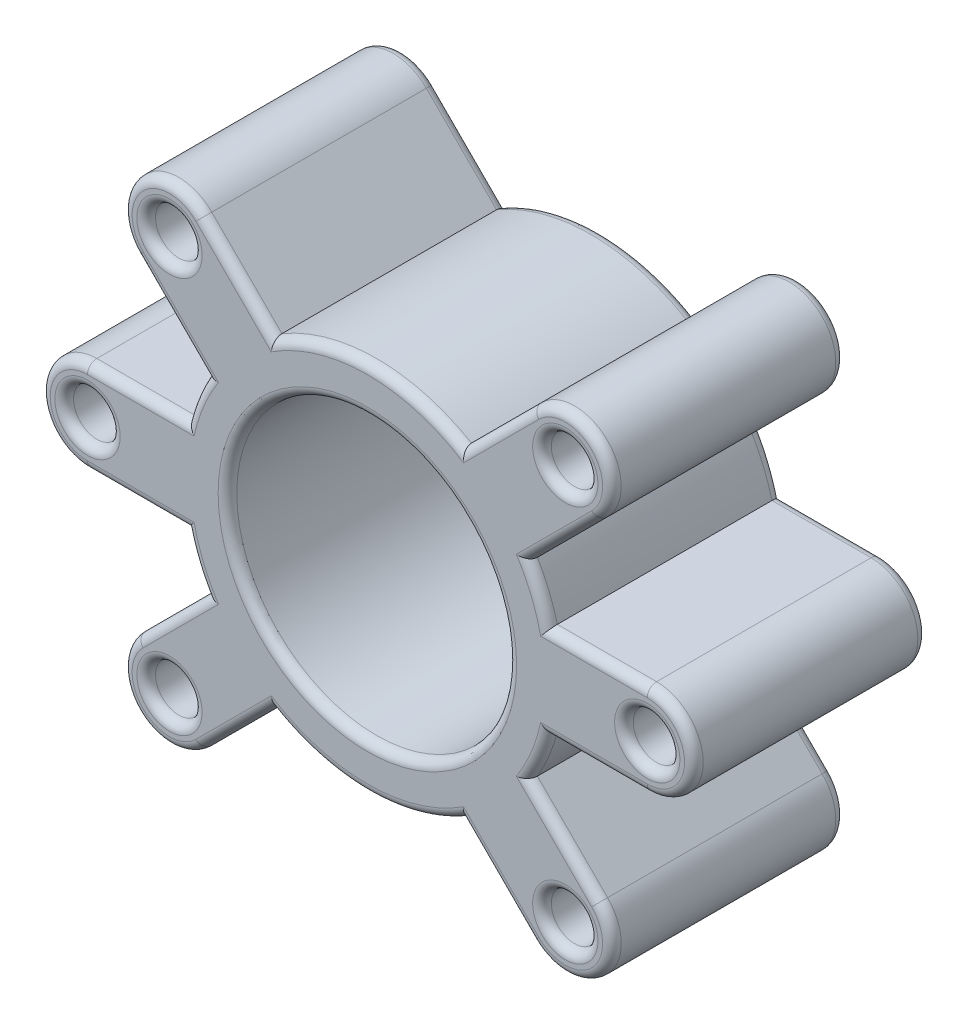
SolidWorks part; units mm, degrees
ref_plane "Front Plane" through (0, 0, 0) normal (0, 0, 1) x (1, 0, 0)
ref_plane "Top Plane" through (0, 0, 0) normal (0, 1, 0) x (1, 0, 0)
ref_plane "Right Plane" through (0, 0, 0) normal (1, 0, 0) x (0, 0, -1)
sketch "Sketch1" plane through (0, 0, 0) normal (0, 0, 1) x (1, 0, 0)
  line L0 (0, 0) -> (68535.6962, 0) construction
  line L1 (0, 0) -> (0, 68535.6962) construction
  line L2 (38.7298, 10) -> (60, 10)
  line L3 (60, -10) -> (38.7298, -10)
  line L4 (34.4572, -20.3151) -> (49.4975, -35.3553)
  line L5 (35.3553, -49.4975) -> (20.3151, -34.4572)
  line L6 (10, -38.7298) -> (10, -60) [skipped]
  line L7 (-10, -60) -> (-10, -38.7298) [skipped]
  line L8 (-20.3151, -34.4572) -> (-35.3553, -49.4975)
  line L9 (-49.4975, -35.3553) -> (-34.4572, -20.3151)
  line L10 (-38.7298, -10) -> (-60, -10)
  line L11 (-60, 10) -> (-38.7298, 10)
  line L12 (-34.4572, 20.3151) -> (-49.4975, 35.3553)
  line L13 (-35.3553, 49.4975) -> (-20.3151, 34.4572)
  line L14 (-10, 38.7298) -> (-10, 60) [skipped]
  line L15 (10, 60) -> (10, 38.7298) [skipped]
  line L16 (20.3151, 34.4572) -> (35.3553, 49.4975)
  line L17 (49.4975, 35.3553) -> (34.4572, 20.3151)
  circle A0 centre (0, 0) radius 30
  circle A1 centre (0, 0) radius 60 construction
  circle A2 centre (0, 0) radius 40
  arc A3 (60, 10) -> (60, -10) centre (60, 0) cw
  circle A4 centre (60, 0) radius 5
  arc A5 (49.4975, -35.3553) -> (35.3553, -49.4975) centre (42.4264, -42.4264) cw
  circle A6 centre (42.4264, -42.4264) radius 5
  arc A7 (10, -60) -> (-10, -60) centre (0, -60) cw [skipped]
  circle A8 centre (0, -60) radius 5 [skipped]
  arc A9 (-35.3553, -49.4975) -> (-49.4975, -35.3553) centre (-42.4264, -42.4264) cw
  circle A10 centre (-42.4264, -42.4264) radius 5
  arc A11 (-60, -10) -> (-60, 10) centre (-60, 0) cw
  circle A12 centre (-60, 0) radius 5
  arc A13 (-49.4975, 35.3553) -> (-35.3553, 49.4975) centre (-42.4264, 42.4264) cw
  circle A14 centre (-42.4264, 42.4264) radius 5
  arc A15 (-10, 60) -> (10, 60) centre (0, 60) cw [skipped]
  circle A16 centre (0, 60) radius 5 [skipped]
  arc A17 (35.3553, 49.4975) -> (49.4975, 35.3553) centre (42.4264, 42.4264) cw
  circle A18 centre (42.4264, 42.4264) radius 5
  point P13 (0, 0)
  point P14 (-22.4992, 40.3603)
  point P16 (0, 0)
  point P60 (0, 0)
  point P61 (0, 0)
  dimension "D1" = 60
  dimension "D2" = 80
  dimension "D3" = 120
  dimension "D4" = 10
  dimension "D5" = 10
  dimension "D6" = 8
extrude "Boss-Extrude1" add sketch "Sketch1" along normal mid plane 50 contours A13 L12 A2 L13 A14 | A11 L10 A2 L11 A12 | A9 L8 A2 L9 A10 | A5 L4 A2 L5 A6 | A3 L2 A2 L3 A4 | A17 L16 A2 L17 A18 | A2 A0
fillet "Fillet1" radius 2 62 edges at (-55, 0, 25) (-55, 0, -25) (-37.4264, -42.4264, 25) (-37.4264, -42.4264, -25) (47.4264, -42.4264, 25) (47.4264, -42.4264, -25) (65, 0, 25) (65, 0, -25) (47.4264, 42.4264, 25) (47.4264, 42.4264, -25) (30, 0, 25) (30, 0, -25) (-27.8352, 41.9773, -25) (-27.8352, 41.9773, 25) (0, 40, 25) (0, 40, -25) (27.8352, 41.9773, -25) (27.8352, 41.9773, 25) (49.4975, 49.4975, -25) (49.4975, 49.4975, 25) (41.9773, 27.8352, -25) (41.9773, 27.8352, 25) (36.9552, 15.3073, 25) (36.9552, 15.3073, -25) (49.3649, 10, -25) (49.3649, 10, 25) (70, 0, -25) (70, 0, 25) (49.3649, -10, -25) (49.3649, -10, 25) (36.9552, -15.3073, 25) (36.9552, -15.3073, -25) (41.9773, -27.8352, -25) (41.9773, -27.8352, 25) (49.4975, -49.4975, -25) (49.4975, -49.4975, 25) (27.8352, -41.9773, -25) (27.8352, -41.9773, 25) (0, -40, 25) (0, -40, -25) (-27.8352, -41.9773, -25) (-27.8352, -41.9773, 25) (-49.4975, -49.4975, -25) (-49.4975, -49.4975, 25) (-41.9773, -27.8352, -25) (-41.9773, -27.8352, 25) (-36.9552, -15.3073, 25) (-36.9552, -15.3073, -25) (-49.3649, -10, -25) (-49.3649, -10, 25) (-70, 0, -25) (-70, 0, 25) (-49.3649, 10, -25) (-49.3649, 10, 25) (-36.9552, 15.3073, 25) (-36.9552, 15.3073, -25) (-41.9773, 27.8352, -25) (-41.9773, 27.8352, 25) (-49.4975, 49.4975, -25) (-49.4975, 49.4975, 25) (-37.4264, 42.4264, 25) (-37.4264, 42.4264, -25)
